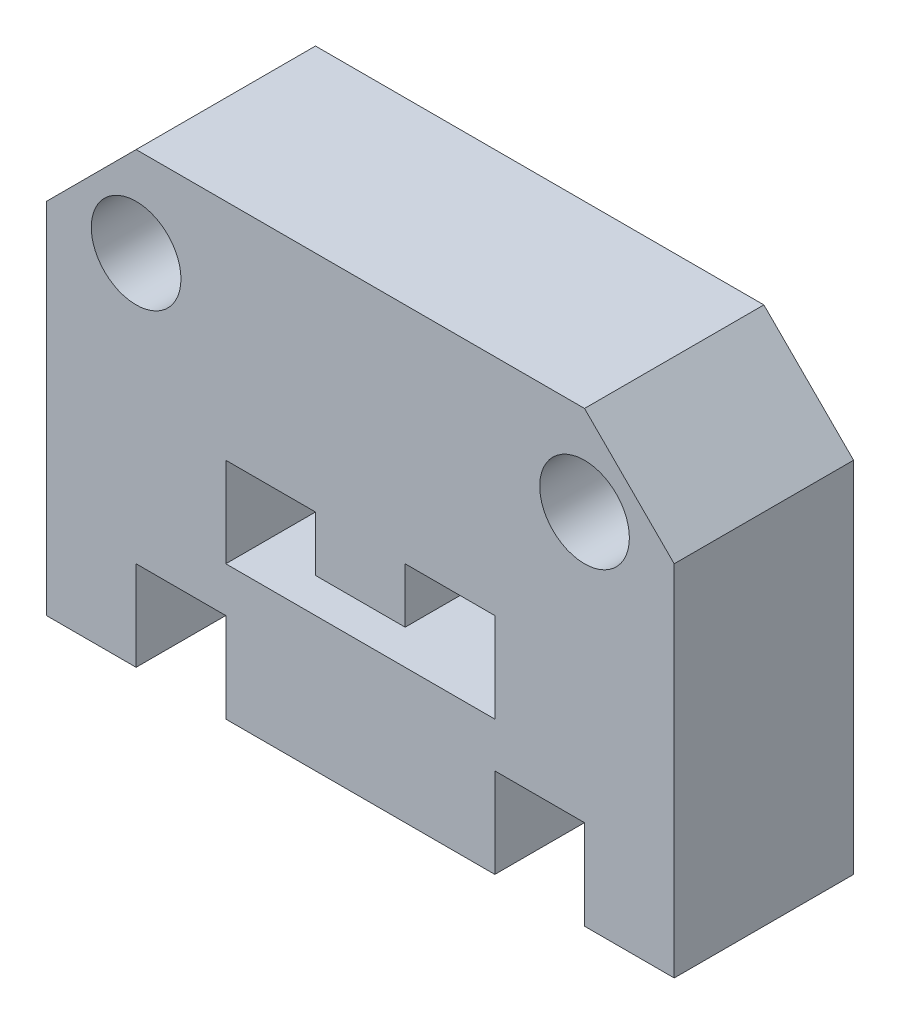
SolidWorks part; units mm, degrees
ref_plane "Front Plane" through (0, 0, 0) normal (0, 0, 1) x (1, 0, 0)
ref_plane "Top Plane" through (0, 0, 0) normal (0, 1, 0) x (1, 0, 0)
ref_plane "Right Plane" through (0, 0, 0) normal (1, 0, 0) x (0, 0, -1)
sketch "Sketch1" plane through (0, 0, 0) normal (0, 0, 1) x (1, 0, 0)
  line L0 (-5, 0) -> (5, 0)
  line L1 (0, 0) -> (0, -3.8744) construction
  line L2 (-15, -3.8744) -> (15, -3.8744)
  line L3 (-15, -3.8744) -> (-15, 6.1256)
  line L4 (-15, 6.1256) -> (-5, 6.1256)
  line L5 (-5, 6.1256) -> (-5, 0)
  line L7 (-15, -18.8744) -> (15, -18.8744)
  line L8 (-15, -18.8744) -> (-15, -8.8744)
  line L9 (-15, -8.8744) -> (-25, -8.8744)
  line L10 (-25, -8.8744) -> (-25, -18.8744)
  line L11 (-25, -18.8744) -> (-35, -18.8744)
  line L12 (-35, -18.8744) -> (-35, 21.1256)
  line L15 (-35, 21.1256) -> (-25, 31.1256)
  line L16 (-25, 31.1256) -> (25, 31.1256)
  line L19 (35, 21.1256) -> (25, 31.1256)
  line L20 (35, -18.8744) -> (35, 21.1256)
  line L21 (25, -18.8744) -> (35, -18.8744)
  line L22 (25, -8.8744) -> (25, -18.8744)
  line L23 (15, -8.8744) -> (25, -8.8744)
  line L24 (15, -18.8744) -> (15, -8.8744)
  line L25 (5, 6.1256) -> (5, 0)
  line L26 (15, 6.1256) -> (5, 6.1256)
  line L27 (15, -3.8744) -> (15, 6.1256)
  circle A0 centre (-25, 21.1256) radius 5
  circle A1 centre (25, 21.1256) radius 5
  point P4 (0, 0)
  point P9 (0, -3.8744)
  point P15 (0, -18.8744)
extrude "Boss-Extrude1" add sketch "Sketch1" along normal blind 20
